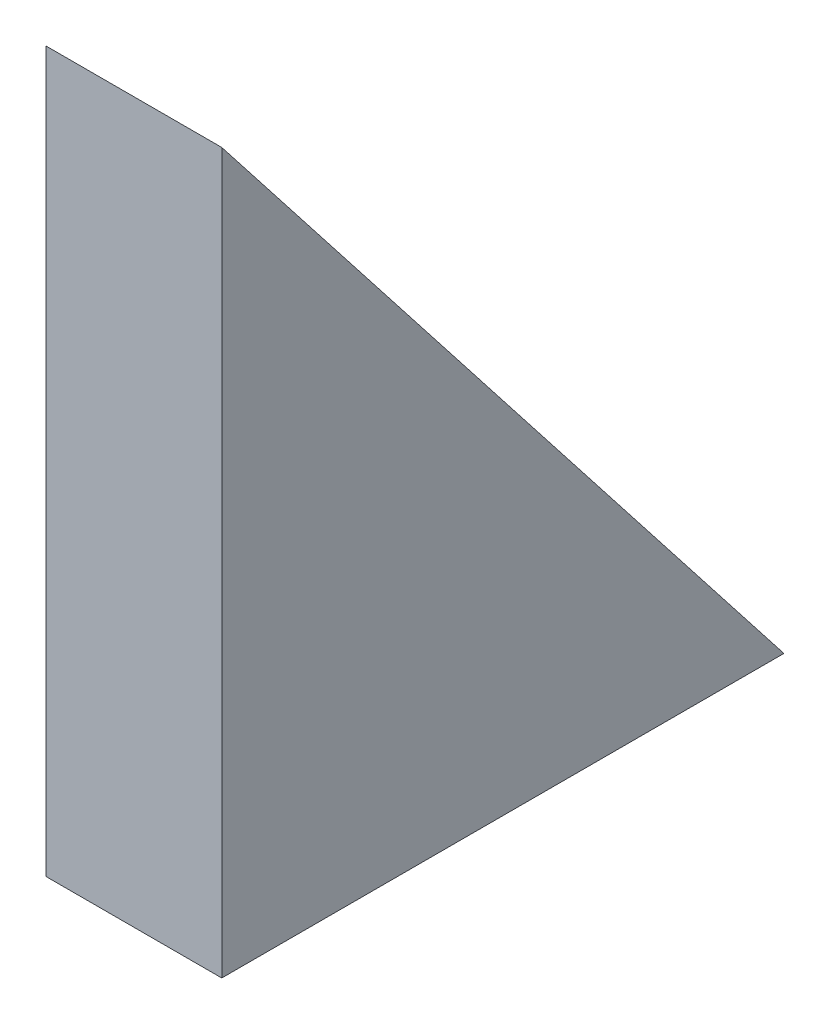
SolidWorks part; units mm, degrees
ref_plane "Front Plane" through (0, 0, 0) normal (0, 0, 1) x (1, 0, 0)
ref_plane "Top Plane" through (0, 0, 0) normal (0, 1, 0) x (1, 0, 0)
ref_plane "Right Plane" through (0, 0, 0) normal (1, 0, 0) x (0, 0, -1)
sketch "Sketch1" plane through (0, 0, 0) normal (1, 0, 0) x (0, 0, -1)
  line L0 (0, 0) -> (0, 65)
  line L1 (0, 65) -> (50.8, 0)
  line L2 (50.8, 0) -> (0, 0)
  dimension "D1" = 50.8
  dimension "D2" = 65
extrude "Boss-Extrude1" add sketch "Sketch1" along normal mid plane 15.875
